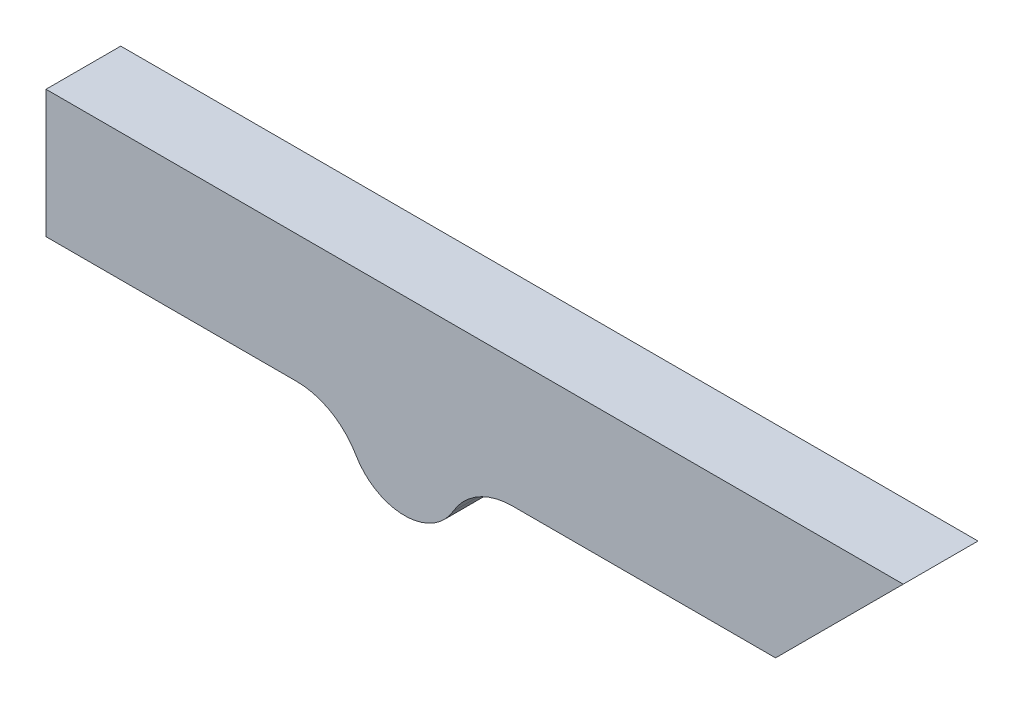
SolidWorks part; units mm, degrees
ref_plane "Front Plane" through (0, 0, 0) normal (0, 0, 1) x (1, 0, 0)
ref_plane "Top Plane" through (0, 0, 0) normal (0, 1, 0) x (1, 0, 0)
ref_plane "Right Plane" through (0, 0, 0) normal (1, 0, 0) x (0, 0, -1)
sketch "Sketch1" plane through (0, 0, 0) normal (0, 0, 1) x (1, 0, 0)
  line L23 (23.3379, 10.61) -> (25.3879, 12.66)
  line L25 (25.4879, 12.76) -> (23.2379, 10.51) construction
  line L27 (23.2379, 10.61) -> (19.1135, 10.61)
  line L28 (15.6494, 10.61) -> (11.625, 10.61)
  line L29 (11.625, 10.61) -> (11.625, 12.66)
  line L30 (11.625, 12.66) -> (25.4879, 12.66)
  line L31 (23.3379, 10.61) -> (19.1135, 10.61)
  line L32 (15.6494, 10.61) -> (11.625, 10.61)
  line L33 (11.625, 10.61) -> (11.625, 12.66)
  line L34 (11.625, 12.66) -> (25.3879, 12.66)
  arc A12 (19.1135, 10.61) -> (18.1609, 10.06) centre (19.1135, 9.51) ccw
  arc A13 (16.602, 10.06) -> (18.1609, 10.06) centre (17.3815, 10.51) ccw
  arc A14 (16.602, 10.06) -> (15.6494, 10.61) centre (15.6494, 9.51) ccw
  arc A15 (19.1135, 10.61) -> (18.1609, 10.06) centre (19.1135, 9.51) ccw
  arc A16 (16.602, 10.06) -> (18.1609, 10.06) centre (17.3815, 10.51) ccw
  arc A17 (16.602, 10.06) -> (15.6494, 10.61) centre (15.6494, 9.51) ccw
  dimension "D1" = 0.1
extrude "Boss-Extrude1" add sketch "Sketch1" along normal up to surface (1.2 mm away)
